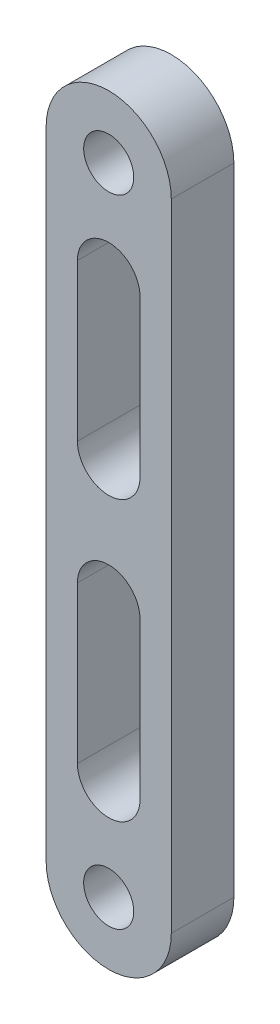
SolidWorks part; units mm, degrees
ref_plane "Front Plane" through (0, 0, 0) normal (0, 0, 1) x (1, 0, 0)
ref_plane "Top Plane" through (0, 0, 0) normal (0, 1, 0) x (1, 0, 0)
ref_plane "Right Plane" through (0, 0, 0) normal (1, 0, 0) x (0, 0, -1)
sketch "Sketch1" plane through (0, 0, 0) normal (0, 0, 1) x (1, 0, 0)
  line L0 (0, -50.8) -> (0, 50.8) construction
  line L1 (-10, -50.8) -> (-10, 50.8)
  line L2 (10, -50.8) -> (10, 50.8)
  line L3 (0, -34.8) -> (0, -9.8) construction
  line L4 (-5, -34.8) -> (-5, -9.8)
  line L5 (5, -34.8) -> (5, -9.8)
  line L6 (0, 34.8) -> (0, 9.8) construction
  line L7 (5, 34.8) -> (5, 9.8)
  line L8 (-5, 34.8) -> (-5, 9.8)
  line L9 (-5, 22.3) -> (5, 22.3) construction
  line L10 (-5, -22.3) -> (5, -22.3) construction
  line L11 (-4, -50.8) -> (-5, -34.8) construction
  line L12 (-4, 50.8) -> (-5, 34.8) construction
  arc A0 (-10, -50.8) -> (10, -50.8) centre (0, -50.8) ccw
  arc A1 (10, 50.8) -> (-10, 50.8) centre (0, 50.8) ccw
  circle A2 centre (0, -50.8) radius 4
  circle A3 centre (0, 50.8) radius 4
  arc A4 (-5, -34.8) -> (5, -34.8) centre (0, -34.8) ccw
  arc A5 (5, -9.8) -> (-5, -9.8) centre (0, -9.8) ccw
  arc A6 (5, 34.8) -> (-5, 34.8) centre (0, 34.8) ccw
  arc A7 (-5, 9.8) -> (5, 9.8) centre (0, 9.8) ccw
  point P2 (0, 0)
  point P14 (0, -22.3)
  point P19 (0, 22.3)
  dimension "D3" = 8
  dimension "D1" = 101.6
  dimension "D2" = 20
  dimension "D4" = 10
  dimension "20" = 25
  dimension "D6" = 16
extrude "Boss-Extrude1" add sketch "Sketch1" along normal blind 10
